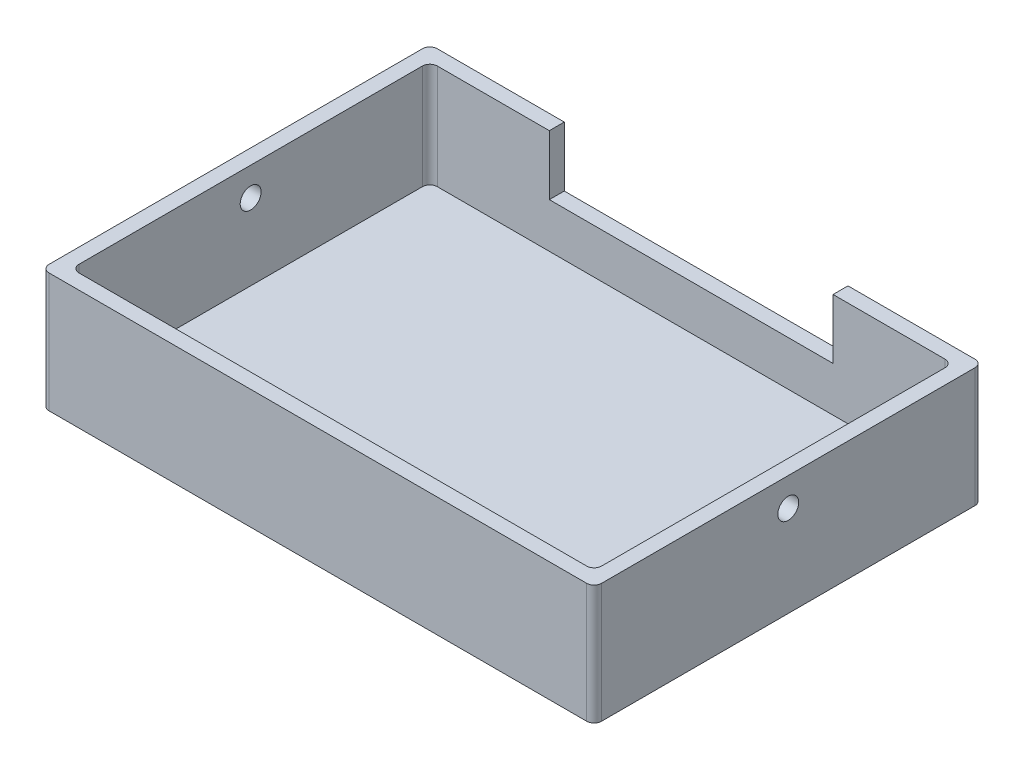
SolidWorks part; units mm, degrees
material "ABS"
ref_plane "Front Plane" through (0, 0, 0) normal (0, 0, 1) x (1, 0, 0)
ref_plane "Top Plane" through (0, 0, 0) normal (0, 1, 0) x (1, 0, 0)
ref_plane "Right Plane" through (0, 0, 0) normal (1, 0, 0) x (0, 0, -1)
sketch "Sketch2" plane through (0, 0, 0) normal (0, 1, 0) x (1, 0, 0)
  line L0 (0, 0) -> (-102346.2979, 0) construction
  line L1 (0, 0) -> (0, 102346.2979) construction
  line L3 (-180, -130) -> (180, -130)
  line L4 (-185, -125) -> (-185, 125)
  line L5 (-180, 130) -> (180, 130)
  line L6 (185, -125) -> (185, 125)
  line L7 (0, 130) -> (0, -130) construction
  line L8 (-185, 0) -> (185, 0) construction
  arc A0 (-180, -130) -> (-185, -125) centre (-180, -125) cw
  arc A1 (180, -130) -> (185, -125) centre (180, -125) ccw
  arc A2 (180, 130) -> (185, 125) centre (180, 125) cw
  arc A3 (-185, 125) -> (-180, 130) centre (-180, 125) cw
  point P5 (0, 0)
  point P11 (-185, -130)
  point P14 (185, -130)
  point P20 (-185, 130)
  dimension "D3" = 5
  dimension "D1" = 370
  dimension "D2" = 260
extrude "Boss-Extrude1" add sketch "Sketch2" along normal blind 10
sketch "Sketch3" plane through (0, 10, 0) normal (0, 1, 0) x (1, 0, 0)
  line L0 (0, 0) -> (-50000, 0) construction
  line L1 (0, 0) -> (0, 50000) construction
  line L3 (180, 130) -> (-180, 130)
  line L4 (185, 125) -> (185, -125)
  line L5 (180, -130) -> (-180, -130)
  line L6 (-185, 125) -> (-185, -125)
  line L7 (0, -130) -> (0, 130) construction
  line L8 (185, 0) -> (-185, 0) construction
  line L9 (170, 120) -> (-170, 120)
  line L10 (175, 115) -> (175, -115)
  line L11 (170, -120) -> (-170, -120)
  line L12 (-175, 115) -> (-175, -115)
  line L13 (0, -120) -> (0, 120) construction
  line L14 (175, 0) -> (-175, 0) construction
  arc A0 (180, 130) -> (185, 125) centre (180, 125) cw
  arc A1 (170, 120) -> (175, 115) centre (170, 115) cw
  arc A2 (175, -115) -> (170, -120) centre (170, -115) cw
  arc A3 (185, -125) -> (180, -130) centre (180, -125) cw
  arc A4 (-170, -120) -> (-175, -115) centre (-170, -115) cw
  arc A5 (-180, -130) -> (-185, -125) centre (-180, -125) cw
  arc A6 (-170, 120) -> (-175, 115) centre (-170, 115) ccw
  arc A7 (-180, 130) -> (-185, 125) centre (-180, 125) ccw
  point P5 (0, 0)
  point P9 (0, 0)
  point P15 (185, 130)
  point P22 (185, -130)
  point P27 (-185, -130)
  dimension "D5" = 5
  dimension "D1" = 10
  dimension "D2" = 10
  dimension "D3" = 370
  dimension "D4" = 260
extrude "Boss-Extrude2" add sketch "Sketch3" along normal blind 70
sketch "Sketch5" plane through (0, 0, -130) normal (0, 0, -1) x (-1, 0, 0)
  line L0 (0, 0) -> (0, 50000) construction
  line L1 (-180, 80) -> (180, 80) construction
  line L2 (95, 120) -> (-95, 120)
  line L3 (95, 120) -> (95, 40)
  line L4 (95, 40) -> (-95, 40)
  line L5 (-95, 120) -> (-95, 40)
  line L6 (0, 40) -> (0, 120) construction
  line L7 (95, 80) -> (-95, 80) construction
  point P3 (0, 80)
  dimension "D1" = 190
  dimension "D2" = 80
extrude "Cut-Extrude1" cut sketch "Sketch5" against normal blind 70
sketch "Sketch6" plane through (185, 0, 0) normal (1, 0, 0) x (0, 0, -1)
  line L0 (0, 0) -> (0, 50000) construction
  line L1 (-125, 80) -> (125, 80) construction
  circle A0 centre (0, 61) radius 7
  dimension "D1" = 14
  dimension "D2" = 19
extrude "Cut-Extrude2" cut sketch "Sketch6" against normal through all
